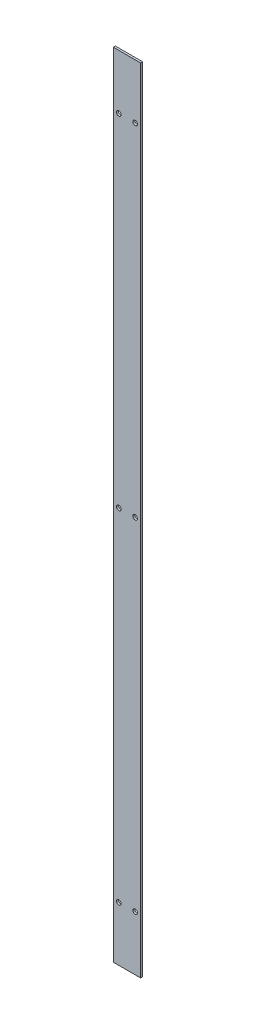
SolidWorks part; units mm, degrees
other "Top Cover Joint Strip 1"
ref_plane "Front Plane" through (0, 0, 0) normal (0, 0, 1) x (1, 0, 0)
ref_plane "Top Plane" through (0, 0, 0) normal (0, 1, 0) x (1, 0, 0)
ref_plane "Right Plane" through (0, 0, 0) normal (1, 0, 0) x (0, 0, -1)
sketch3d "Main Profile Sketch datum points"
  point P0 (0, 0, 110)
  point P1 (10, 0, 110)
  point P2 (0, 10, 110)
ref_plane "Main Profile Sketch plane" through (0, 0, 110) normal (0, 0, 1) x (1, 0, 0)
sketch "Main Profile Sketch" plane through (0, 0, 110) normal (0, 0, 1) x (1, 0, 0)
  line L0 (-150.5, 290) -> (-130.5, 290)
  line L1 (-130.5, 290) -> (-130.5, -290)
  line L2 (-150.5, -290) -> (-130.5, -290)
  line L3 (-150.5, 290) -> (-150.5, -290)
  circle A0 centre (-146.5, -250) radius 1.7
  circle A1 centre (-134.5, -250) radius 1.7
  circle A2 centre (-146.5, 0) radius 1.7
  circle A3 centre (-146.5, 250) radius 1.7
  circle A4 centre (-134.5, 0) radius 1.7
  circle A5 centre (-134.5, 250) radius 1.7
extrude "Main Extrusion" add sketch "Main Profile Sketch" against normal blind 1.5 separate body
